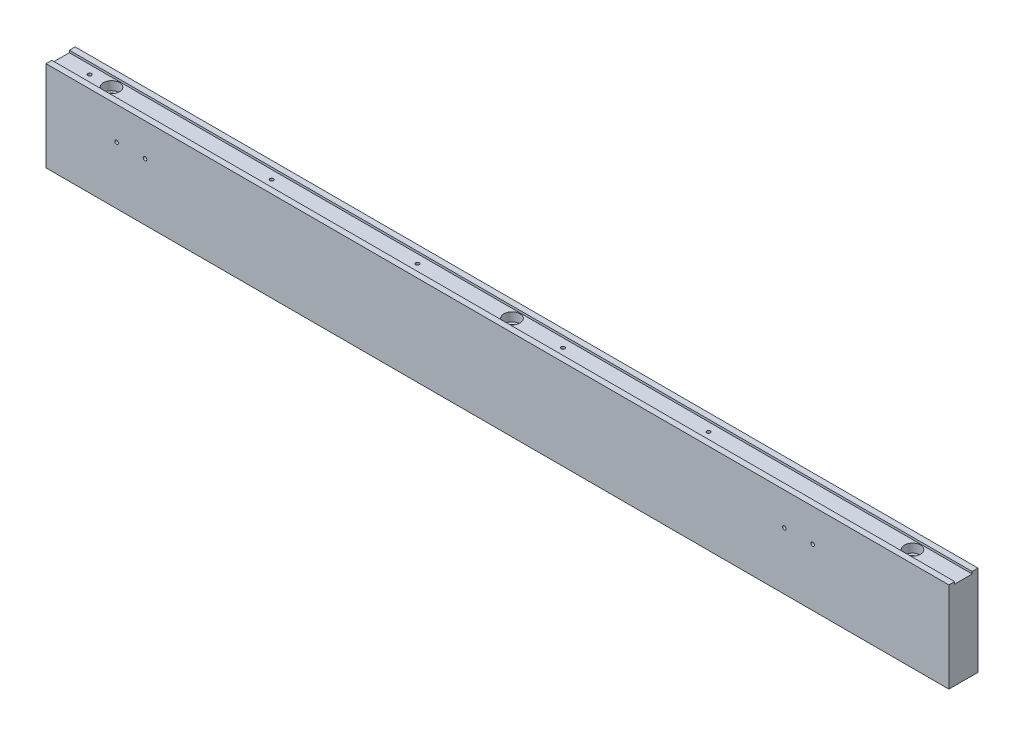
SolidWorks part; units mm, degrees
material "铝材"
ref_plane "前基準面" through (0, 0, 0) normal (0, 0, 1) x (1, 0, 0)
ref_plane "上基準面" through (0, 0, 0) normal (0, 1, 0) x (1, 0, 0)
ref_plane "右基準面" through (0, 0, 0) normal (1, 0, 0) x (0, 0, -1)
sketch "草图1" plane through (0, 0, 0) normal (0, 0, 1) x (1, 0, 0)
  line L1 (0, 0) -> (620, 0)
  line L2 (0, 0) -> (0, 62)
  line L3 (0, 62) -> (620, 62)
  line L4 (620, 0) -> (620, 62)
  dimension "D1" = 620
  dimension "D2" = 62
extrude "凸台-拉伸1" add sketch "草图1" along normal blind 20
sketch "草图2" plane through (620, 0, 0) normal (1, 0, 0) x (0, 0, -1)
  line L0 (-20, 62) -> (0, 62) construction
  line L1 (-4, 62) -> (-16, 62)
  line L2 (-4, 62) -> (-4, 60.5)
  line L3 (-4, 60.5) -> (-16, 60.5)
  line L4 (-16, 62) -> (-16, 60.5)
  line L5 (-10, 62) -> (-10, 81.6017) construction
  dimension "D1" = 12
  dimension "D2" = 1.5
extrude "切除-拉伸1" cut sketch "草图2" against normal through all
hole_wizard "M6 六角凹头螺钉的柱形沉头孔1" positions "草图4" profile "草图3" counterbore size "M6" standard "ISO" end condition through all
sketch "草图4" plane through (0, 60.5, 0) normal (0, 1, 0) x (-1, 0, 0)
  line L0 (-310, 20) -> (-310, 0) construction
  line L1 (-620, 20) -> (0, 20) construction
  line L2 (-620, 0) -> (0, 0) construction
  line L3 (-310, 10) -> (0, 10) construction
  line L4 (0, 16) -> (0, 4) construction
  point P0 (-35, 10)
  point P1 (-310, 10)
  point P3 (-585, 10)
  dimension "D1" = 550
sketch "草图3" plane through (35, 60.5, 10) normal (1, 0, 0) x (0, 0, 1)
  line L0 (0, 0) -> (0, 60.5)
  line L1 (0, 60.5) -> (3.5, 60.5)
  line L3 (3.5, 60.5) -> (3.5, 6)
  line L4 (3.5, 6) -> (5.5, 6)
  line L5 (5.5, 6) -> (5.5, 0)
  line L7 (5.5, 0) -> (0, 0)
  line L11 (0, -6.35) -> (0, 107.95) construction
  dimension "通孔孔直径" = 7
  dimension "通孔孔深度" = 60.5
  dimension "柱形沉头孔直径" = 11
  dimension "柱形沉头孔深度" = 6
hole_wizard "M3 螺纹孔1" positions "草图6" profile "草图5" tap size "M3" standard "ISO"
sketch "草图6" plane through (0, 60.5, 0) normal (0, 1, 0) x (-1, 0, 0)
  point P0 (-20, 10)
  point P7 (-445, 10)
  point P10 (-345, 10)
  point P13 (-245, 10)
  point P16 (-145, 10)
sketch "草图5" plane through (20, 60.5, 10) normal (1, 0, 0) x (0, 0, 1)
  line L0 (0, 0) -> (0, 8.2511)
  line L1 (0, 8.2511) -> (1.25, 7.5)
  line L2 (1.25, 7.5) -> (1.25, 0)
  line L5 (1.25, 0) -> (0, 0)
  line L10 (0, 8.2511) -> (-1.25, 7.5) construction
  line L11 (0, -6.35) -> (0, 107.95) construction
  dimension "螺纹孔钻头直径" = 2.5
  dimension "螺纹孔钻头深度" = 7.5
  dimension "导头角度" = 118
cosmetic thread "孔螺蚊线1" parameters "D1"=6, "D2"=3
cosmetic thread "孔螺蚊线2" parameters "D1"=6, "D2"=3
cosmetic thread "孔螺蚊线3" parameters "D1"=6, "D2"=3
cosmetic thread "孔螺蚊线4" parameters "D1"=6, "D2"=3
cosmetic thread "孔螺蚊线5" parameters "D1"=6, "D2"=3
hole_wizard "M3 螺纹孔2" positions "草图8" profile "草图7" tap size "M3" standard "ISO"
sketch "草图8" plane through (0, 0, 20) normal (0, 0, 1) x (1, 0, 0)
  line L0 (620, 0) -> (620, 62) construction
  line L1 (620, 62) -> (0, 62) construction
  point P0 (48.5, 39.5)
  point P1 (68, 39.5)
  point P3 (507, 39.5)
  point P5 (526.5, 39.5)
  dimension "D1" = 19.5
  dimension "D2" = 93.5
  dimension "D3" = 22.5
  dimension "D4" = 19.5
  dimension "D5" = 439
sketch "草图7" plane through (48.5, 39.5, 20) normal (1, 0, 0) x (0, -1, 0)
  line L0 (0, 0) -> (0, 8.2511)
  line L1 (0, 8.2511) -> (1.25, 7.5)
  line L2 (1.25, 7.5) -> (1.25, 0)
  line L5 (1.25, 0) -> (0, 0)
  line L10 (0, 8.2511) -> (-1.25, 7.5) construction
  line L11 (0, -6.35) -> (0, 107.95) construction
  dimension "螺纹孔钻头直径" = 2.5
  dimension "螺纹孔钻头深度" = 7.5
  dimension "导头角度" = 118
cosmetic thread "孔螺蚊线7" parameters "D1"=6, "D2"=3
cosmetic thread "孔螺蚊线8" parameters "D1"=6, "D2"=3
cosmetic thread "孔螺蚊线9" parameters "D1"=6, "D2"=3
cosmetic thread "孔螺蚊线10" parameters "D1"=6, "D2"=3
